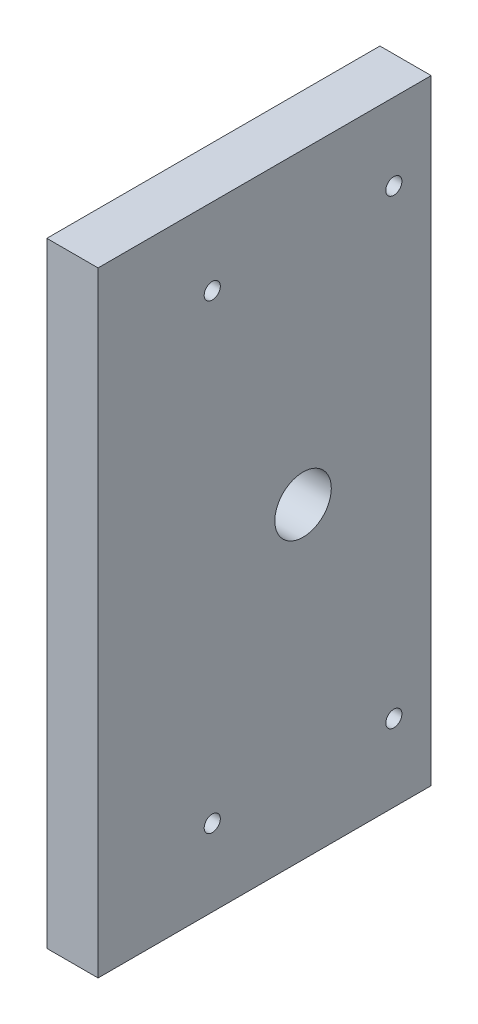
SolidWorks part; units mm, degrees
ref_plane "Plan de face" through (0, 0, 0) normal (0, 0, 1) x (1, 0, 0)
ref_plane "Plan de dessus" through (0, 0, 0) normal (0, 1, 0) x (1, 0, 0)
ref_plane "Plan de droite" through (0, 0, 0) normal (1, 0, 0) x (0, 0, -1)
sketch "Esquisse1" plane through (0, 0, 0) normal (1, 0, 0) x (0, 0, -1)
  line L1 (-41.275, 76.2) -> (41.275, 76.2)
  line L2 (-41.275, 76.2) -> (-41.275, -76.2)
  line L3 (-41.275, -76.2) -> (41.275, -76.2)
  line L4 (41.275, 76.2) -> (41.275, -76.2)
  line L5 (-41.275, 76.2) -> (41.275, -76.2) construction
  line L6 (-41.275, -76.2) -> (41.275, 76.2) construction
  point P0 (0, 0)
  dimension "D1" = 82.55
  dimension "D2" = 152.4
extrude "Boss.-Extru.1" add sketch "Esquisse1" along normal blind 12.7
sketch "Esquisse2" plane through (12.7, 0, 0) normal (1, 0, 0) x (0, 0, -1)
  line L0 (-41.275, 76.2) -> (-41.275, -76.2) construction
  line L1 (32.025, -57.15) -> (-12.975, -57.15) construction
  line L2 (32.025, -57.15) -> (32.025, 57.15) construction
  line L3 (32.025, 57.15) -> (-12.975, 57.15) construction
  line L4 (-12.975, -57.15) -> (-12.975, 57.15) construction
  line L5 (41.275, 76.2) -> (-41.275, 76.2) construction
  circle A0 centre (-12.975, 57.15) radius 2
  circle A1 centre (32.025, 57.15) radius 2
  circle A2 centre (-12.975, -57.15) radius 2
  circle A3 centre (32.025, -57.15) radius 2
  point P0 (0, 0)
  dimension "D3" = 4
  dimension "D1" = 45
  dimension "D2" = 114.3
  dimension "D4" = 28.3
  dimension "D5" = 19.05
extrude "Enlèv. mat.-Extru.1" cut sketch "Esquisse2" against normal through all
sketch "Esquisse3" plane through (12.7, 0, 0) normal (1, 0, 0) x (0, 0, -1)
  line L0 (-41.275, 76.2) -> (-41.275, -76.2) construction
  line L1 (41.275, 76.2) -> (-41.275, 76.2) construction
  circle A5 centre (9.525, 0) radius 7
  dimension "D1" = 14
  dimension "D2" = 50.8
  dimension "D3" = 76.2
extrude "Enlèv. mat.-Extru.2" cut sketch "Esquisse3" against normal through all
sketch "Esquisse5" plane through (0, 0, 0) normal (-1, 0, 0) x (0, 0, 1)
  line L0 (41.275, 76.2) -> (41.275, -76.2) construction
  line L1 (-41.275, 76.2) -> (41.275, 76.2) construction
  circle A0 centre (-9.525, 0) radius 7.5
  dimension "D1" = 15
  dimension "D2" = 50.8
  dimension "D3" = 76.2
extrude "Enlèv. mat.-Extru.4" cut sketch "Esquisse5" against normal blind 1
